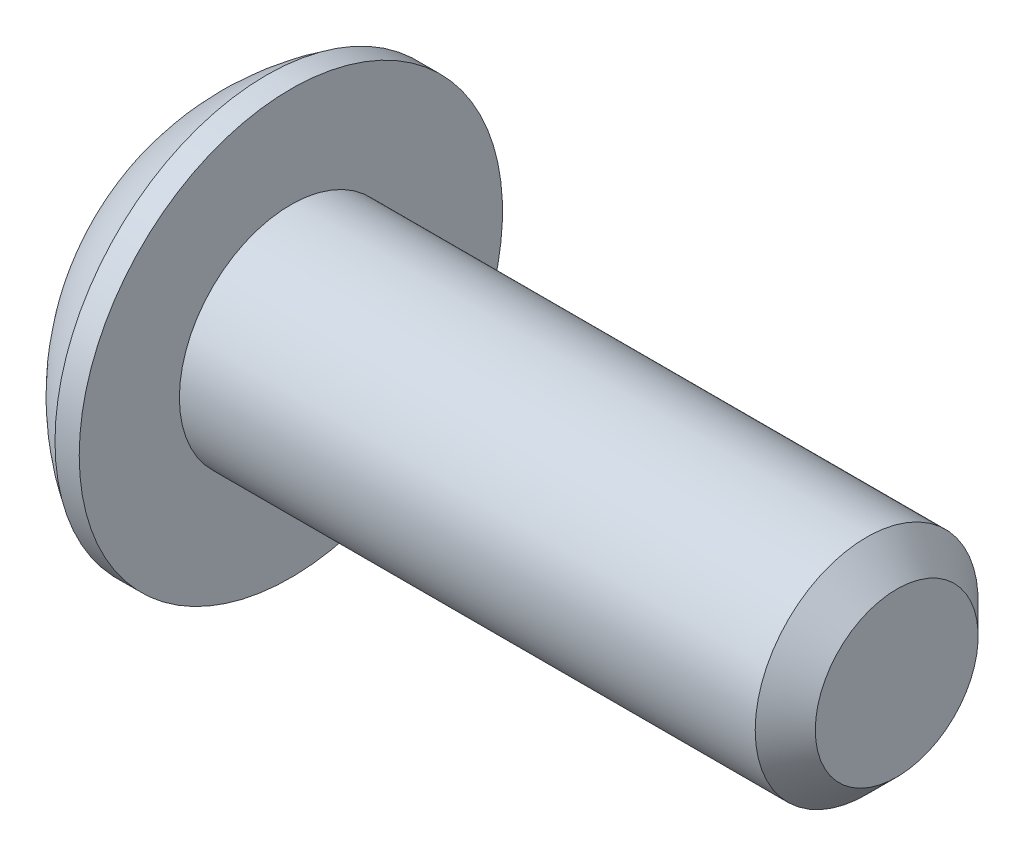
SolidWorks part; units mm, degrees
ref_plane "Plane1" through (0, 0, 0) normal (0, 0, 1) x (1, 0, 0)
ref_plane "Plane2" through (0, 0, 0) normal (0, 1, 0) x (1, 0, 0)
ref_plane "Plane3" through (0, 0, 0) normal (1, 0, 0) x (0, 0, -1)
sketch "BodySke" plane through (0, 0, 0) normal (0, 0, 1) x (1, 0, 0)
  line L0 (11.3792, 0) -> (11.3792, 1.2802)
  line L1 (10.9068, 1.7526) -> (1.8542, 1.7526)
  line L2 (1.8542, 1.7526) -> (1.8542, 3.3274)
  line L3 (1.8542, 3.3274) -> (1.4732, 3.3274)
  line L4 (0, 0) -> (101.6, 0) construction
  line L5 (1.8542, -3.3274) -> (1.4732, -3.3274) construction
  line L6 (55.6768, -1.7526) -> (1.8542, -1.7526) construction
  line L7 (11.3792, 0) -> (0, 0)
  line L8 (0, 1.6637) -> (0, -1.6637) construction
  line L9 (0, 0) -> (0, 1.6637)
  line L10 (11.3792, 1.2802) -> (10.9068, 1.7526)
  line L11 (11.3792, -1.2802) -> (10.9068, -1.7526) construction
  line L12 (2.6467, 9.525) -> (2.6467, -1.7526) construction
  line L13 (1.8542, 9.525) -> (1.8542, -1.7526) construction
  arc A1 (0, 1.6637) -> (1.4732, 3.3274) centre (3.5549, 0) cw
  dimension "Diameter" = 3.5052
  dimension "Length" = 9.525
  dimension "Head_dia" = 6.6548
  dimension "D1" = 3.3274
  dimension "Head_ht" = 1.8542
  dimension "Head_side_ht" = 0.381
  dimension "Minor_dia" = 2.5603
  dimension "Body_ch_ang" = 45
  dimension "Advance" = 0.7925
  dimension "Thread_nom" = 9.525
revolve "BaseBody" add sketch "BodySke" angle 360 about L4
cosmetic thread "ThreadCosmetic" [suppressed] parameters "Thread_length"=8.7325, "Thread_minor"=2.5603
sketch "Sketch2" plane through (0, 0, 0) normal (0, 0, 1) x (1, 0, 0)
  line L0 (0, 0.9906) -> (1.1176, 0.9906)
  line L1 (1.1176, 0.9906) -> (1.6895, 0)
  line L3 (1.6895, 0) -> (0, 0)
  line L4 (0, 0) -> (0, 0.9906)
  line L5 (0, -0.9906) -> (1.1176, -0.9906) construction
  line L6 (0, 0) -> (47.625, 0) construction
  dimension "D2" = 60
  dimension "PreBroach_depth" = 1.1176
  dimension "PreBroach_dia" = 1.9812
revolve "PreBroach" cut sketch "Sketch2" angle 360 about L6
sketch "Sketch3" plane through (0, 0, 0) normal (1, 0, 0) x (0, 0, -1)
  line L0 (-0.9906, -0.5719) -> (-0.9906, 0.5719)
  line L1 (-0.9906, 0.5719) -> (0, 1.1438)
  line L2 (0, 1.1438) -> (0.9906, 0.5719)
  line L3 (0.9906, 0.5719) -> (0.9906, -0.5719)
  line L4 (0.9906, -0.5719) -> (0, -1.1438)
  line L5 (0, -1.1438) -> (-0.9906, -0.5719)
  dimension "Hex_size" = 1.9812
  dimension "D3" = 1.9812
  dimension "D1" = 0.9906
  dimension "D2" = 0.9906
extrude "Hex" cut sketch "Sketch3" along normal blind 1.1176
sketch "Sketch4" plane through (0, 9.525, 0) normal (1, 0, 0) x (0, 0, -1)
  line L0 (0, -9.525) -> (1.2446, -9.525)
  line L1 (0, -9.525) -> (6.1484, -5.9752) construction
  line L2 (0, -9.525) -> (0.6223, -8.4471)
  line L3 (1.0085, -9.2654) -> (1.19, -9.1606)
  line L4 (0.7291, -8.7814) -> (0.9106, -8.6766)
  arc A0 (1.0085, -9.2654) -> (0.7291, -8.7814) centre (0, -9.525) ccw
  arc A1 (1.2446, -9.525) -> (1.19, -9.1606) centre (0, -9.525) ccw
  arc A2 (0.6223, -8.4471) -> (0.9106, -8.6766) centre (0, -9.525) cw
  dimension "Spline_n_dim" = 2.0828
  dimension "Spline_m_dim" = 2.4892
  dimension "D1" = 30
  dimension "D2" = 60
  dimension "Spline_p_dim" = 0.5588
  dimension "D3" = 0.2794
extrude "Spline" [suppressed] cut sketch "Sketch4" along normal blind 1.1176
pattern_circular "CirPattern1" [suppressed] count 6 every 60 about axis through (0, 0, 0) along (1, 0, 0)
sketch "ThdSchSke" plane through (0, 0, 0) normal (0, 0, 1) x (1, 0, 0)
  line L0 (2.6467, -1.2802) -> (2.3159, -1.7526)
  line L1 (2.6467, -1.2802) -> (2.9775, -1.7526)
  line L2 (2.9775, -1.7526) -> (2.9775, -2.1907)
  line L3 (-3.175, 0) -> (5.1513, 0) construction
  line L5 (2.9775, -2.1907) -> (2.3159, -2.1907)
  line L6 (2.3159, -2.1907) -> (2.3159, -1.7526)
  dimension "Diameter" = 3.5052
  dimension "Thread_minor" = 2.5603
  dimension "SideAngle" = 55
  dimension "VeeAngle" = 70
  dimension "Overcut" = 4.3815
  dimension "Start" = 2.6467
revolve "ThreadSchematic" [suppressed] cut sketch "ThdSchSke" angle 360 about L3
pattern_linear "ThdSchPat" [suppressed]
equation "\"D1@BodySke\" = \"Head_dia@BodySke\" * .5"
equation "\"Thread_minor@ThreadCosmetic\" = \"Minor_dia@BodySke\""
equation "\"D1@Sketch3\" = \"Hex_size@Sketch3\" / 2"
equation "\"D2@Sketch3\" = \"D1@Sketch3\""
equation "\"D3@Sketch3\" = \"Hex_size@Sketch3\""
equation "\"D3@Sketch4\" = \"Spline_p_dim@Sketch4\" / 2"
equation "\"D1@Sketch4\" = \"D2@Sketch4\" / 2"
equation "\"Thread_length@ThreadCosmetic\" = ((sgn( (\"Length@BodySke\" - \"Advance@BodySke\" ) - \"Thread_nom@BodySke\" )-1)*( (\"Length@BodySke\" - \"Advance@BodySke\" ) - \"Thread_nom@BodySke\" ))/-2+ \"Thread_nom@BodySke\""
equation "\"Thread_minor@ThdSchSke\" = \"Minor_dia@BodySke\""
equation "\"Diameter@ThdSchSke\" = \"Diameter@BodySke\""
equation "\"Overcut@ThdSchSke\" = \"Diameter@BodySke\" * 1.25"
equation "\"Start@ThdSchSke\" = \"Head_ht@BodySke\" + \"Length@BodySke\" - \"Thread_length@ThreadCosmetic\"  '---Non-countersunk---"
equation "\"Num_threads@ThdSchPat\" = int( \"Thread_length@ThreadCosmetic\" / \"Advance@BodySke\" + 0.999 )  + 1"
equation "\"Advance@ThdSchPat\" = \"Thread_length@ThreadCosmetic\" /  (\"Num_threads@ThdSchPat\" - 1) 'relax it"
equation "\"Num_threads@ThdSchPat\" = \"Num_threads@ThdSchPat\" - sgn( \"Num_threads@ThdSchPat\" - 1) '---chamfered tips only---"
